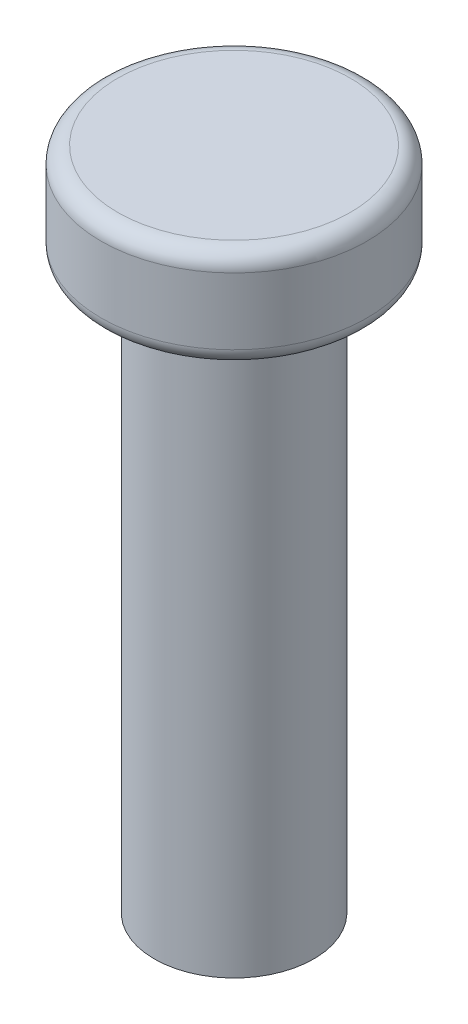
SolidWorks part; units mm, degrees
ref_plane "Front Plane" through (0, 0, 0) normal (0, 0, 1) x (1, 0, 0)
ref_plane "Top Plane" through (0, 0, 0) normal (0, 1, 0) x (1, 0, 0)
ref_plane "Right Plane" through (0, 0, 0) normal (1, 0, 0) x (0, 0, -1)
sketch "Sketch1" plane through (0, 0, 0) normal (0, 1, 0) x (1, 0, 0)
  circle A0 centre (0, 0) radius 2.4
  dimension "D1" = 4.8
extrude "Boss-Extrude1" add sketch "Sketch1" along normal blind 17
sketch "Sketch2" plane through (0, 17, 0) normal (0, 1, 0) x (1, 0, 0)
  circle A0 centre (0, 0) radius 4
  dimension "D1" = 8
extrude "Boss-Extrude2" add sketch "Sketch2" along normal blind 3
fillet "Fillet5" radius 0.5 2 edges at (0, 17, 4) (0, 20, 4)
